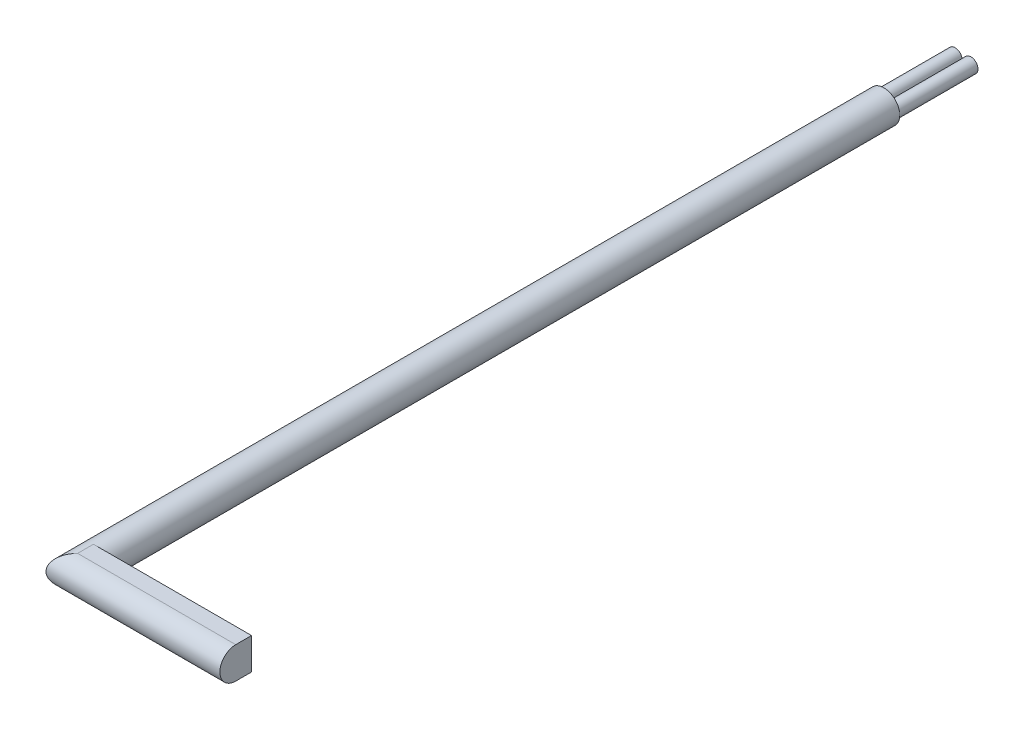
SolidWorks part; units mm, degrees
ref_plane "Front Plane" through (0, 0, 0) normal (0, 0, 1) x (1, 0, 0)
ref_plane "Top Plane" through (0, 0, 0) normal (0, 1, 0) x (1, 0, 0)
ref_plane "Right Plane" through (0, 0, 0) normal (1, 0, 0) x (0, 0, -1)
sketch "Sketch1" plane through (0, 0, 0) normal (0, 0, 1) x (1, 0, 0)
  circle A0 centre (0, 0) radius 1
  dimension "D1" = 2
extrude "Boss-Extrude1" add sketch "Sketch1" along normal blind 50
sketch "Sketch2" plane through (0, 0, 50) normal (0, 0, 1) x (1, 0, 0)
  line L1 (0, 1) -> (10, 1)
  line L2 (0, 1) -> (0, -1)
  line L3 (0, -1) -> (10, -1)
  line L4 (10, 1) -> (10, -1)
  circle A0 centre (0, 0) radius 1 construction
  dimension "D1" = 2
  dimension "D2" = 10
extrude "Boss-Extrude2" add sketch "Sketch2" along normal blind 2
sketch "Sketch3" plane through (0, 0, 50) normal (0, 0, 1) x (1, 0, 0)
  line L1 (0, -1) -> (0, 1)
  line L2 (0, -1) -> (0, 1)
  arc A1 (0, 1) -> (0, -1) centre (0, 0) ccw
  arc A2 (0, 1) -> (0, -1) centre (0, 0) ccw
  dimension "D1" = 0
extrude "Boss-Extrude3" add sketch "Sketch3" along normal blind 2
sketch "Sketch4" plane through (10, 0, 0) normal (1, 0, 0) x (0, 0, -1)
  line L0 (-51, 1) -> (-51, -1)
  line L1 (-52, 1) -> (-50, 1) construction
  line L2 (-52, -1) -> (-50, -1) construction
  line L3 (-51, 1) -> (-52, 1)
  line L4 (-52, 1) -> (-52, -1)
  line L5 (-52, -1) -> (-51, -1)
  arc A0 (-51, 1) -> (-51, -1) centre (-51, 0) ccw
  line M2 (-50, 1) -> (-52, 1)
  line M3 (-52, 1) -> (-52, -1)
  line M4 (-52, -1) -> (-50, -1)
extrude "Cut-Extrude1" cut sketch "Sketch4" against normal up to surface (10 mm away) contours A0 M2 M3 | A0 L4 M4
sketch "Sketch5" plane through (0, 0, 0) normal (0, 0, -1) x (-1, 0, 0)
  line L0 (0, 0) -> (0.5, 0)
  line L1 (0, 0) -> (-0.5, 0)
  circle A0 centre (0.5, 0) radius 0.45
  circle A1 centre (-0.5, 0) radius 0.45
  dimension "D3" = 0.9
  dimension "D4" = 0.9
  dimension "D1" = 0.5
  dimension "D2" = 0.5
extrude "Boss-Extrude4" add sketch "Sketch5" along normal blind 5
